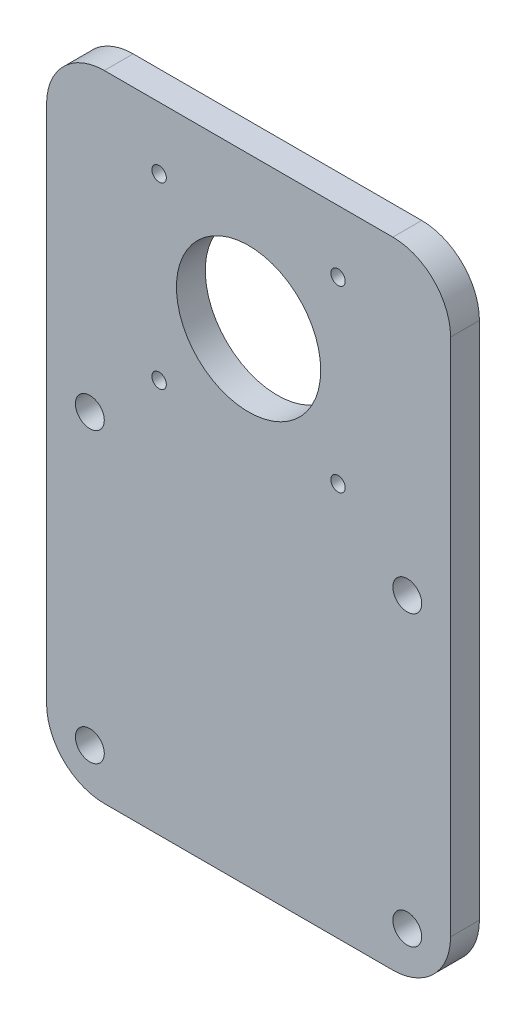
SolidWorks part; units mm, degrees
ref_plane "Front Plane" through (0, 0, 0) normal (0, 0, 1) x (1, 0, 0)
ref_plane "Top Plane" through (0, 0, 0) normal (0, 1, 0) x (1, 0, 0)
ref_plane "Right Plane" through (0, 0, 0) normal (1, 0, 0) x (0, 0, -1)
sketch "Sketch1" plane through (0, 0, 0) normal (0, 0, 1) x (1, 0, 0)
  line L0 (-56.0075, -69.8441) -> (13.9925, -69.8441) construction
  line L1 (-56.0075, 32.6559) -> (13.9925, 32.6559)
  line L2 (-56.0075, 32.6559) -> (-56.0075, -77.3441)
  line L3 (-56.0075, -77.3441) -> (13.9925, -77.3441)
  line L4 (13.9925, 32.6559) -> (13.9925, -77.3441)
  line L5 (-56.0075, -19.8441) -> (13.9925, -19.8441) construction
  line L6 (-21.0075, 32.6559) -> (-21.0075, -19.8441) construction
  line L7 (-21.0075, 6.4059) -> (-42.2307, -14.8136) construction
  line L8 (-42.2307, -14.8136) -> (1.1304, 28.5399) construction
  line L9 (1.1304, 28.5399) -> (-21.0075, 6.4059) construction
  line L10 (-21.0075, 6.4059) -> (-0.0032, -14.6022) construction
  line L11 (-0.0032, -14.6022) -> (-39.8259, 25.2275) construction
  circle A0 centre (-48.5075, -19.8441) radius 2.5
  circle A1 centre (6.4925, -19.8441) radius 2.5
  circle A2 centre (-48.5075, -69.8441) radius 2.5
  circle A3 centre (6.4925, -69.8441) radius 2.5
  circle A4 centre (-21.0075, 6.4059) radius 12.5
  circle A5 centre (-36.5075, 21.9086) radius 1.25
  circle A6 centre (-5.5075, 21.9031) radius 1.25
  circle A7 centre (-5.5075, -9.0969) radius 1.25
  circle A8 centre (-36.5075, -9.0914) radius 1.25
  dimension "D5" = 7.5
  dimension "D9" = 15.5
  dimension "D10" = 15.5
  dimension "D11" = 15.5
  dimension "D12" = 15.5
  dimension "D1" = 70
  dimension "D2" = 110
  dimension "D3" = 7.5
  dimension "D4" = 50
  dimension "D6" = 7.5
  dimension "D7" = 7.5
  dimension "D8" = 7.5
extrude "Boss-Extrude1" add sketch "Sketch1" along normal blind 5
fillet "Fillet1" radius 10 4 edges at (-56.0075, -77.3441, 2.5) (13.9925, -77.3441, 2.5) (13.9925, 32.6559, 2.5) (-56.0075, 32.6559, 2.5)
